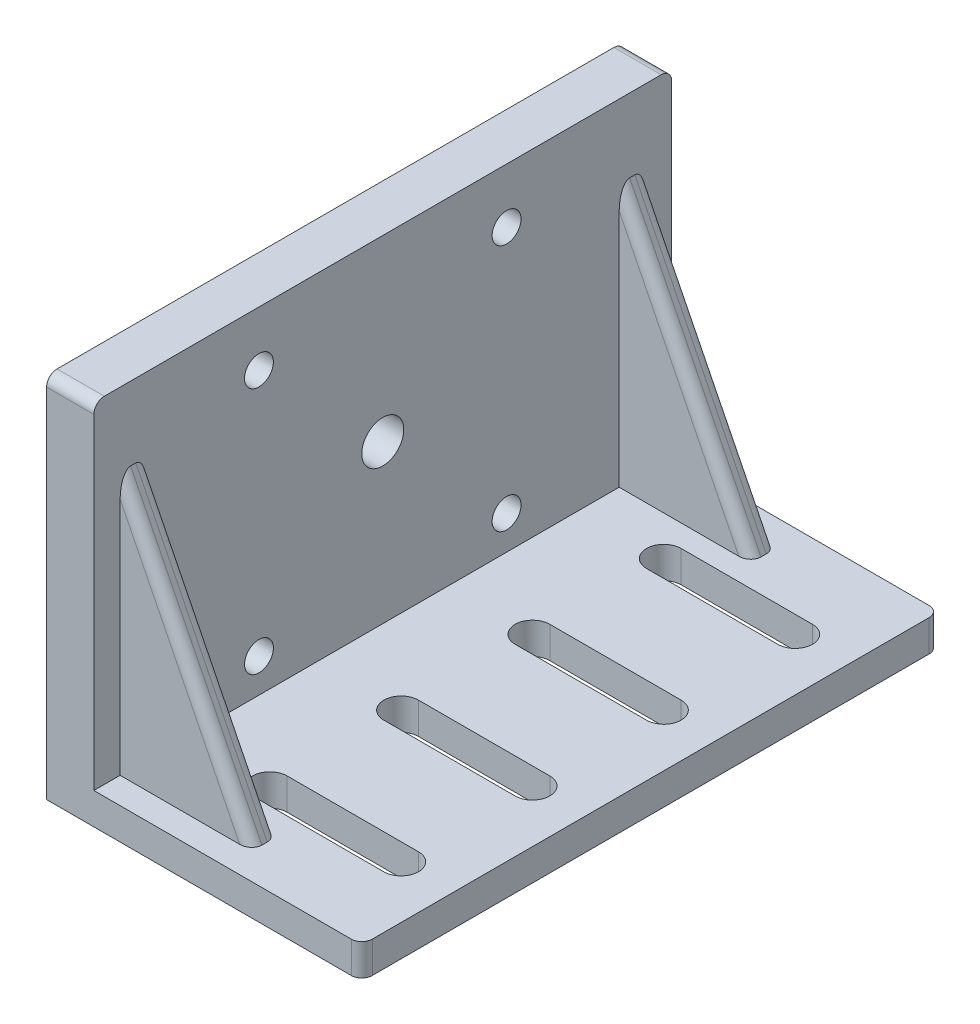
SolidWorks part; units mm, degrees
ref_plane "Front Plane" through (0, 0, 0) normal (0, 0, 1) x (1, 0, 0)
ref_plane "Top Plane" through (0, 0, 0) normal (0, 1, 0) x (1, 0, 0)
ref_plane "Right Plane" through (0, 0, 0) normal (1, 0, 0) x (0, 0, -1)
sketch "Sketch1" plane through (0, 0, 0) normal (0, 0, 1) x (1, 0, 0)
  line L0 (0, 0) -> (60, 0)
  line L3 (9, 6) -> (60, 6)
  line L4 (60, 0) -> (60, 6)
  line L6 (0, 0) -> (0, 70)
  line L7 (0, 70) -> (9, 70)
  line L8 (9, 6) -> (9, 70)
  dimension "D1" = 70
  dimension "D2" = 60
  dimension "D3" = 6
  dimension "D4" = 9
extrude "Boss-Extrude1" add sketch "Sketch1" along normal blind 110
sketch "Sketch2" plane through (0, 0, 0) normal (-1, 0, 0) x (0, 0, 1)
  line L0 (55, 79.5905) -> (55, -29.7242) construction
  line L1 (0, 70) -> (0, 0) construction
  line L2 (110, 0) -> (0, 0) construction
  line L3 (55, 36) -> (115.0643, 36) construction
  circle A0 centre (55, 36) radius 4
  circle A5 centre (78.57, 59.57) radius 2.75
  circle A6 centre (31.43, 59.57) radius 2.75
  circle A7 centre (31.43, 12.43) radius 2.75
  circle A8 centre (78.57, 12.43) radius 2.75
  point P20 (30, 27)
  dimension "D3" = 8
  dimension "D5" = 23.57
  dimension "D6" = 5.5
  dimension "D1" = 55
  dimension "D2" = 36
  dimension "D4" = 23.57
  dimension "D7" = 2
  dimension "D8" = 2
extrude "Cut-Extrude1" cut sketch "Sketch2" against normal up to surface (9 mm away) up to face at (9, 38, 55)
sketch "Sketch3" plane through (0, 6, 0) normal (0, 1, 0) x (1, 0, 0)
  line L0 (0, -110) -> (0, 0) construction
  line L1 (60, 0) -> (9, 0) construction
  line L2 (35.4135, -55) -> (-18.7217, -55) construction
  line L3 (25, -14.2) -> (50, -14.2)
  line L4 (25, -20.8) -> (50, -20.8)
  line L7 (25, -39.2) -> (50, -39.2)
  line L8 (25, -45.8) -> (50, -45.8)
  line L9 (25, -64.2) -> (50, -64.2)
  line L10 (25, -70.8) -> (50, -70.8)
  line L11 (25, -89.2) -> (50, -89.2)
  line L12 (25, -95.8) -> (50, -95.8)
  arc A0 (25, -14.2) -> (25, -20.8) centre (25, -17.5) ccw
  arc A1 (50, -20.8) -> (50, -14.2) centre (50, -17.5) ccw
  arc A4 (50, -45.8) -> (50, -39.2) centre (50, -42.5) ccw [skipped]
  arc A5 (25, -39.2) -> (25, -45.8) centre (25, -42.5) ccw [skipped]
  arc A6 (25, -39.2) -> (25, -45.8) centre (25, -42.5) ccw
  arc A7 (50, -45.8) -> (50, -39.2) centre (50, -42.5) ccw
  arc A8 (25, -64.2) -> (25, -70.8) centre (25, -67.5) ccw
  arc A9 (50, -70.8) -> (50, -64.2) centre (50, -67.5) ccw
  arc A10 (25, -89.2) -> (25, -95.8) centre (25, -92.5) ccw
  arc A11 (50, -95.8) -> (50, -89.2) centre (50, -92.5) ccw
  dimension "D3" = 6.6
  dimension "D1" = 25
  dimension "D2" = 37.5
  dimension "D6" = 55
  dimension "D4" = 2
  dimension "D5" = 2
  dimension "D7" = 4
extrude "Cut-Extrude2" cut sketch "Sketch3" against normal up to surface (6 mm away) up to face at (30, 0, 55)
ref_plane "Plane1" through (0, 0, 55) normal (0, 0, 1) x (1, 0, 0)
ref_plane "Plane2" through (0, 0, 8) normal (0, 0, 1) x (1, 0, 0)
ref_plane "Plane3" through (0, 0, 102) normal (0, 0, 1) x (1, 0, 0)
sketch "Sketch7" plane through (0, 0, 102) normal (0, 0, 1) x (1, 0, 0)
  line L0 (9, 56) -> (34, 6)
  line L1 (9, 6) -> (9, 70) construction
  line L2 (60, 6) -> (9, 6) construction
  line L3 (9, 56) -> (9, 6)
  line L4 (9, 6) -> (34, 6)
  dimension "D1" = 50
  dimension "D2" = 25
extrude "Boss-Extrude2" add sketch "Sketch7" along normal blind 3 and the other way blind 2
sketch "Sketch9" plane through (0, 0, 8) normal (0, 0, 1) x (1, 0, 0)
  line L3 (9, 56) -> (9, 6)
  line L4 (9, 6) -> (34, 6)
  line L5 (34, 6) -> (9, 56)
  line L6 (9, 56) -> (9, 6)
  line L7 (9, 6) -> (34, 6)
  line L8 (34, 6) -> (9, 56)
  dimension "D1" = 0
extrude "Boss-Extrude4" add sketch "Sketch9" along normal blind 2 and the other way blind 3
fillet "Fillet1" radius 2 8 edges at (21.5, 31, 10) (21.5, 31, 5) (21.5, 31, 100) (21.5, 31, 105) (60, 3, 110) (60, 3, 0) (4.5, 70, 110) (4.5, 70, 0)
